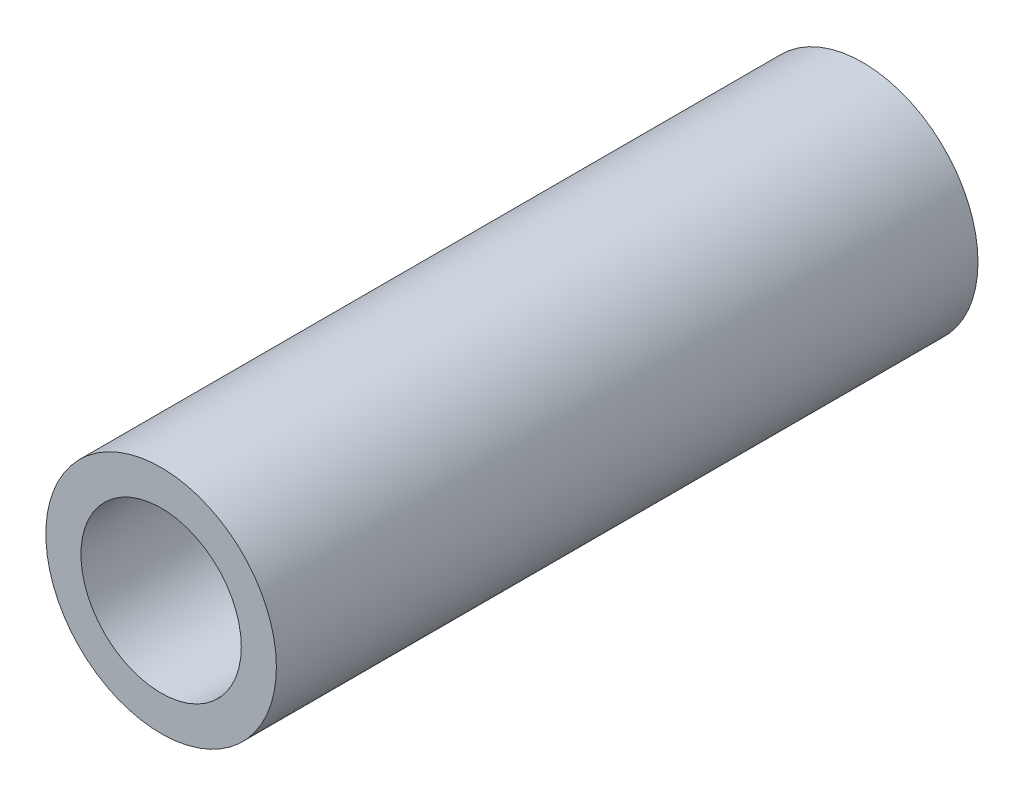
SolidWorks part; units mm, degrees
ref_plane "Front Plane" through (0, 0, 0) normal (0, 0, 1) x (1, 0, 0)
ref_plane "Top Plane" through (0, 0, 0) normal (0, 1, 0) x (1, 0, 0)
ref_plane "Right Plane" through (0, 0, 0) normal (1, 0, 0) x (0, 0, -1)
sketch "Sketch1" plane through (0, 0, 0) normal (0, 0, 1) x (1, 0, 0)
  circle A0 centre (0, 0) radius 5.75
  circle A1 centre (0, 0) radius 4
  dimension "D1" = 11.5
  dimension "D2" = 8
extrude "Boss-Extrude1" add sketch "Sketch1" along normal blind 35
